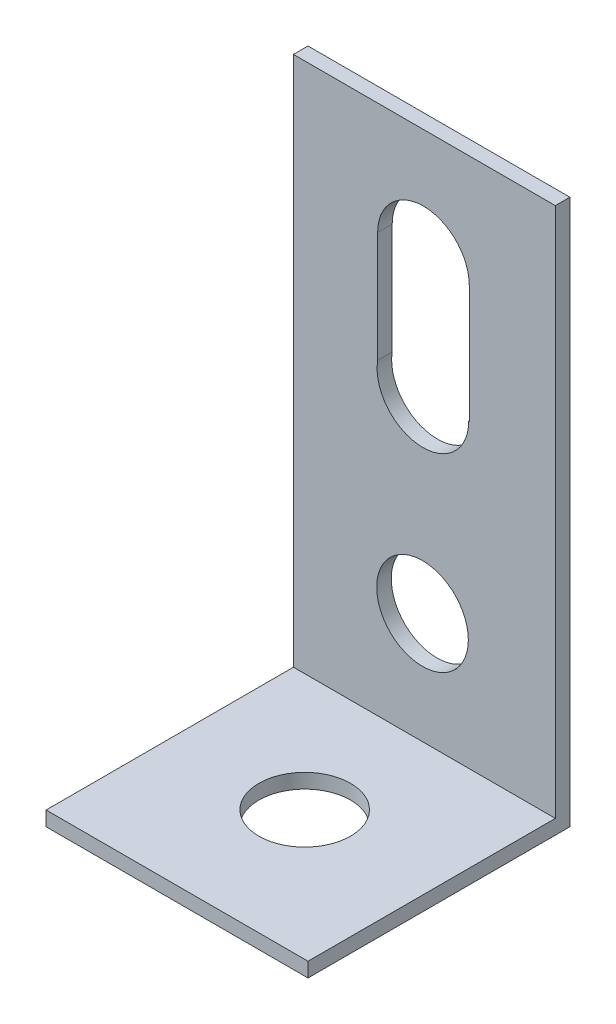
SolidWorks part; units mm, degrees
ref_plane "Front Plane" through (0, 0, 0) normal (0, 0, 1) x (1, 0, 0)
ref_plane "Top Plane" through (0, 0, 0) normal (0, 1, 0) x (1, 0, 0)
ref_plane "Right Plane" through (0, 0, 0) normal (1, 0, 0) x (0, 0, -1)
sketch "Sketch1" plane through (0, 0, 0) normal (0, 1, 0) x (1, 0, 0)
  line L1 (-11.2654, -11.306) -> (11.5946, -11.306)
  line L2 (-11.2654, -11.306) -> (-11.2654, 11.554)
  line L3 (-11.2654, 11.554) -> (11.5946, 11.554)
  line L4 (11.5946, -11.306) -> (11.5946, 11.554)
  line L5 (-11.2654, -11.306) -> (11.5946, 11.554) construction
  line L6 (-11.2654, 11.554) -> (11.5946, -11.306) construction
  point P0 (0, 0)
  dimension "D1" = 22.86
  dimension "D2" = 22.86
extrude "Boss-Extrude1" add sketch "Sketch1" along normal blind 1.27
sketch "Sketch3" plane through (0, 0, 0) normal (0, -1, 0) x (1, 0, 0)
  line L1 (-11.2654, -11.554) -> (11.5946, -11.554)
  line L2 (-11.2654, -11.554) -> (-11.2654, -10.284)
  line L3 (-11.2654, -10.284) -> (11.5946, -10.284)
  line L4 (11.5946, -11.554) -> (11.5946, -10.284)
  dimension "D1" = 1.27
extrude "Boss-Extrude2" add sketch "Sketch3" against normal blind 47.593
sketch "Sketch4" plane through (0, 1.27, 0) normal (0, 1, 0) x (1, 0, 0)
  circle A0 centre (0, 0) radius 4
sketch "Sketch5" plane through (0, 0, -10.284) normal (0, 0, 1) x (1, 0, 0)
  line L0 (-3.9175, 37.7995) -> (-3.9175, 27.5241)
  line L1 (-3.9175, 27.5241) -> (4.0825, 27.5241)
  line L2 (4.0825, 27.5241) -> (4.0825, 37.7995)
  line L3 (-3.9175, 37.7995) -> (4.0825, 37.7995)
  circle A0 centre (0, 10.9619) radius 4
  circle A1 centre (0.0346, 27.5241) radius 4
  circle A2 centre (0.0825, 37.7995) radius 4
  point P10 (0.0825, 37.7995)
extrude "Cut-Extrude2" cut sketch "Sketch4" against normal blind 10 contours A0
extrude "Cut-Extrude3" cut sketch "Sketch5" against normal blind 2.54 contours L3 A2 L0 | L0 A2 L3 | A2 L0 A1 L1 L2 L3 | L1 A1 L0 | L0 A1 L1 | A0
scale "Scale2" bodies to scale 110 scale about origin uniform scaling yes scale factor 2.1
